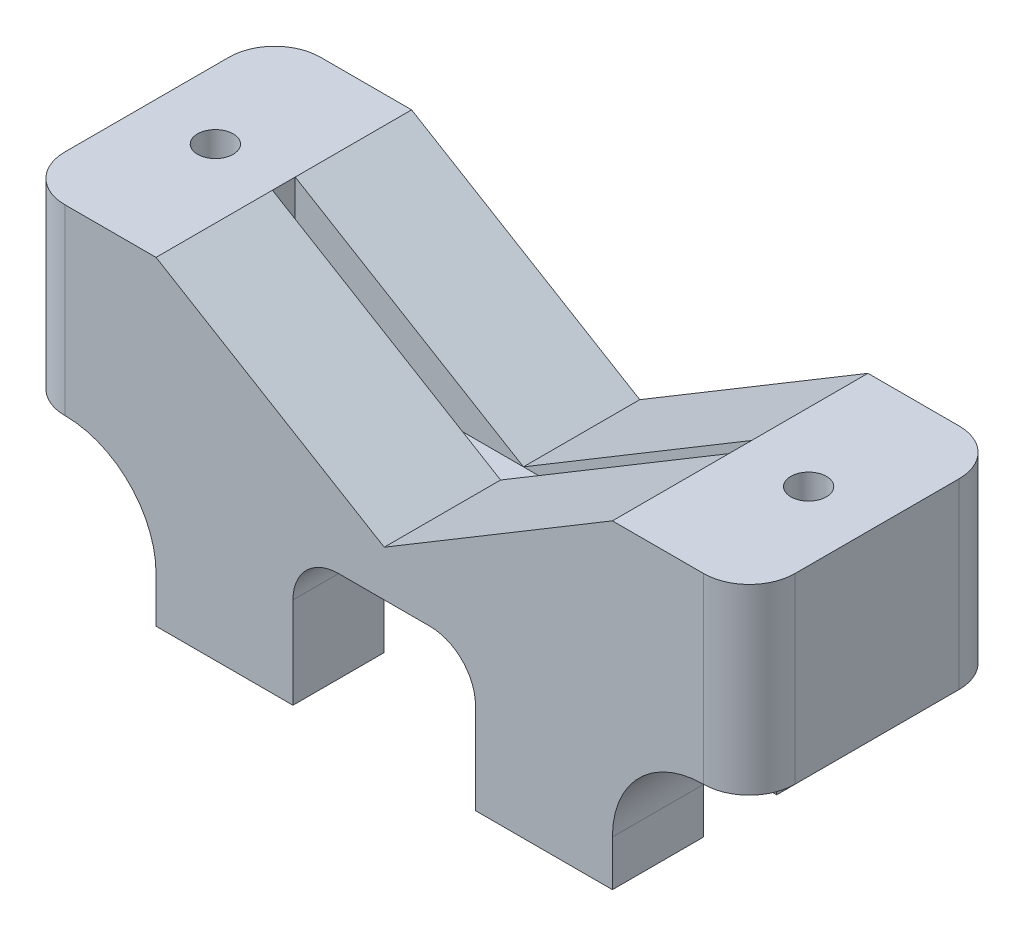
SolidWorks part; units mm, degrees
ref_plane "Front" through (0, 0, 0) normal (0, 0, 1) x (1, 0, 0)
ref_plane "Top" through (0, 0, 0) normal (0, 1, 0) x (1, 0, 0)
ref_plane "Right" through (0, 0, 0) normal (1, 0, 0) x (0, 0, -1)
sketch "Sketch1" plane through (0, 0, 0) normal (0, 1, 0) x (1, 0, 0)
  line L1 (25, -14) -> (-25, -14)
  line L2 (25, -14) -> (25, 14)
  line L3 (25, 14) -> (-25, 14)
  line L4 (-25, -14) -> (-25, 14)
  line L5 (25, -14) -> (-25, 14) construction
  line L6 (25, 14) -> (-25, -14) construction
  line L7 (10, -14) -> (-10, -14) construction
  line L8 (10, -14) -> (10, 14)
  line L9 (10, 14) -> (-10, 14) construction
  line L10 (-10, -14) -> (-10, 14)
  line L11 (10, -14) -> (-10, 14) construction
  line L12 (10, 14) -> (-10, -14) construction
  line L13 (25, -4) -> (-25, -4)
  line L14 (25, -4) -> (25, 4) construction
  line L15 (25, 4) -> (-25, 4)
  line L16 (-25, -4) -> (-25, 4) construction
  line L17 (25, -4) -> (-25, 4) construction
  line L18 (25, 4) -> (-25, -4) construction
  point P0 (0, 0)
  point P6 (0, 0)
  point P11 (0, 0)
  dimension "D1" = 50
  dimension "D2" = 28
  dimension "D3" = 20
  dimension "D4" = 8
extrude "Boss-Extrude1" add sketch "Sketch1" against normal blind 15 contours L15 L10 L3 L4 | L15 L2 L3 L8 | L2 L13 L8 L1 | L10 L13 L4 L1
sketch "Sketch2" plane through (0, 0, 0) normal (0, 1, 0) x (1, 0, 0)
  line L1 (25, -14) -> (-25, -14)
  line L2 (25, -14) -> (25, 14)
  line L3 (25, 14) -> (-25, 14)
  line L4 (-25, -14) -> (-25, 14)
  line L5 (25, -14) -> (-25, 14) construction
  line L6 (25, 14) -> (-25, -14) construction
  point P0 (0, 0)
extrude "Boss-Extrude2" add sketch "Sketch2" along normal blind 5
sketch "Sketch4" plane through (0, 0, 0) normal (0, 1, 0) x (1, 0, 0)
  line L0 (25, 14) -> (-25, 14) construction
  line L1 (40, -14) -> (-40, -14)
  line L2 (40, -14) -> (40, 14)
  line L3 (40, 14) -> (-40, 14)
  line L4 (-40, -14) -> (-40, 14)
  line L5 (40, -14) -> (-40, 14) construction
  line L6 (40, 14) -> (-40, -14) construction
  point P0 (0, 0)
  dimension "D1" = 80
extrude "Boss-Extrude3" add sketch "Sketch4" along normal blind 20
sketch "Sketch5" plane through (0, 0, 0) normal (0, 0, 1) x (1, 0, 0)
  line L0 (-40, 20) -> (40, 20) construction
  line L1 (-25, 35) -> (25, 35)
  line L2 (-25, 35) -> (-25, 5)
  line L3 (-25, 5) -> (25, 5)
  line L4 (25, 35) -> (25, 5)
  line L5 (-25, 35) -> (25, 5) construction
  line L6 (-25, 5) -> (25, 35) construction
  line L7 (0, 5) -> (-25, 20)
  line L8 (0, 5) -> (25, 20)
  line L9 (-25, 20) -> (25, 20)
  point P0 (0, 20)
  dimension "D1" = 30
  dimension "D2" = 50
extrude "Cut-Extrude1" cut sketch "Sketch5" against normal blind 20 and the other way blind 20 contours L9 L7 L8
sketch "Sketch6" plane through (0, 0, 0) normal (0, 0, 1) x (1, 0, 0)
  line L0 (-25, 20) -> (-25, 5)
  line L1 (0, 5) -> (-25, 5)
  line L2 (-25, 20) -> (0, 5)
extrude "Cut-Extrude2" cut sketch "Sketch6" against normal blind 1.25 and the other way blind 1.25
mirror "Mirror1" about plane through (0, 0, 0) normal (1, 0, 0) of "Cut-Extrude2"
ref_plane "Plane1" through (0, 20, 0) normal (0, 1, 0) x (1, 0, 0)
sketch "Sketch7" plane through (0, 20, 0) normal (0, 1, 0) x (1, 0, 0)
  line L1 (-32.5, 10) -> (32.5, 10) construction
  line L2 (-32.5, 10) -> (-32.5, -10) construction
  line L3 (-32.5, -10) -> (32.5, -10) construction
  line L4 (32.5, 10) -> (32.5, -10) construction
  line L5 (-32.5, 10) -> (32.5, -10) construction
  line L6 (-32.5, -10) -> (32.5, 10) construction
  point P0 (0, 0)
  point P6 (32.5, 0)
  point P7 (-32.5, 0)
  point P8 (0, -10)
  point P9 (0, 10)
  dimension "D1" = 20
  dimension "D2" = 65
hole_wizard "M3.5 Clearance Hole1" positions "Sketch12" profile "Sketch13" hole size "M3.5" standard "ISO"
sketch "Sketch12" plane through (0, 20, 0) normal (0, 1, 0) x (1, 0, 0)
  point P0 (32.5, 0)
  point P3 (-32.5, 0)
sketch "Sketch13" plane through (32.5, 20, 0) normal (1, 0, 0) x (0, 0, 1)
  line L0 (0, 0) -> (0, 16.1717)
  line L1 (0, 16.1717) -> (1.95, 15)
  line L2 (1.95, 15) -> (1.95, 0)
  line L5 (1.95, 0) -> (0, 0)
  line L10 (0, 16.1717) -> (-1.95, 15) construction
  line L11 (0, -6.35) -> (0, 107.95) construction
  dimension "Hole Dia." = 3.9
  dimension "Hole Depth" = 15
  dimension "Drill Angle" = 118
fillet "Fillet1" radius 10 4 edges at (-25, 0, 9) (-25, 0, -9) (25, 0, 9) (25, 0, -9)
fillet "Fillet2" radius 5 4 edges at (10, 0, 9) (-10, 0, -9) (-10, 0, 9) (10, 0, -9)
fillet "Fillet3" radius 5 4 edges at (-40, 10, -14) (-40, 10, 14) (40, 10, 14) (40, 10, -14)
